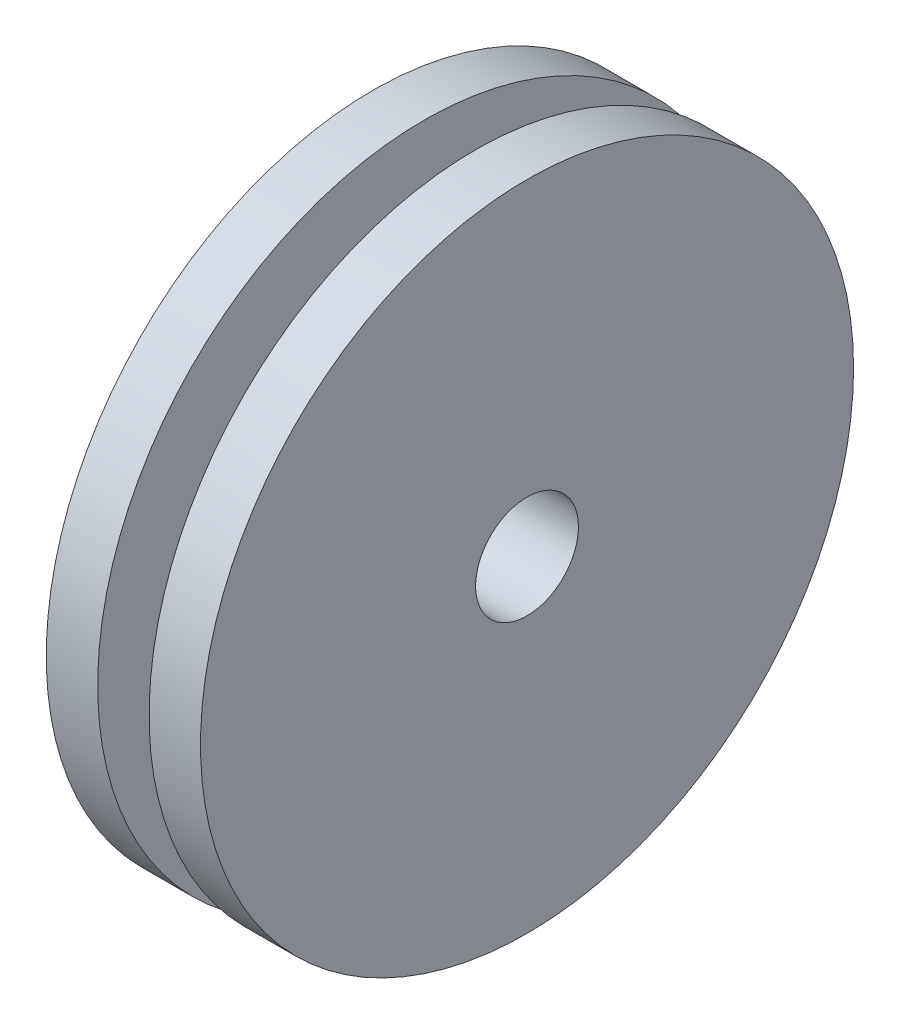
SolidWorks part; units mm, degrees
ref_plane "Plano frontal" through (0, 0, 0) normal (0, 0, 1) x (1, 0, 0)
ref_plane "Plano superior" through (0, 0, 0) normal (0, 1, 0) x (1, 0, 0)
ref_plane "Plano direito" through (0, 0, 0) normal (1, 0, 0) x (0, 0, -1)
sketch "Esboço1" plane through (0, 0, 0) normal (0, 0, 1) x (1, 0, 0)
  line L0 (-6, 4) -> (-6, 25.4)
  line L1 (-6, 25.4) -> (-2, 25.4)
  line L2 (-2, 25.4) -> (-2, 19.4)
  line L3 (-2, 19.4) -> (2, 19.4)
  line L4 (0, 0) -> (-65.1747, 0) construction
  line L5 (0, 0) -> (0, 68.0298) construction
  line L6 (-6, 4) -> (6, 4)
  line L7 (2, 25.4) -> (2, 19.4)
  line L8 (6, 25.4) -> (2, 25.4)
  line L9 (6, 4) -> (6, 25.4)
  point P11 (0, 4)
  point P12 (0, 19.4)
  dimension "D1" = 6
  dimension "D2" = 50.8
  dimension "D3" = 4
  dimension "D4" = 4
  dimension "D5" = 8
revolve "Revolução1" add sketch "Esboço1" angle 360 about L4
